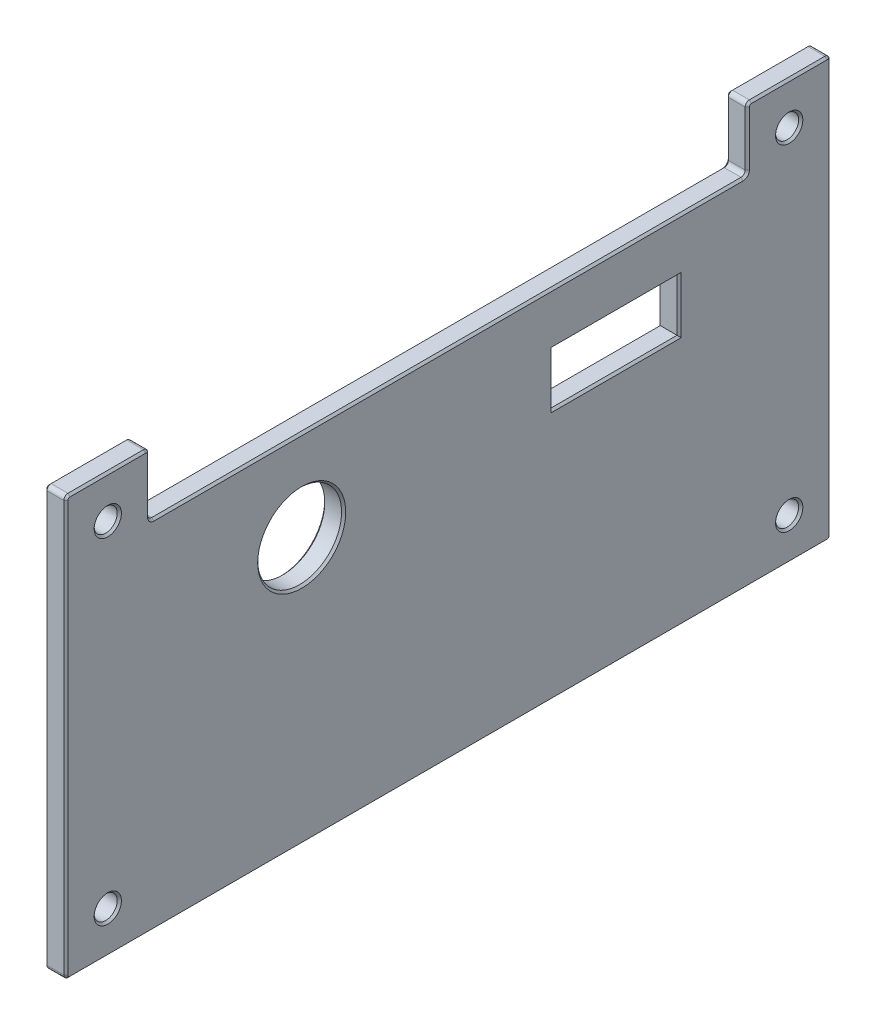
SolidWorks part; units mm, degrees
ref_plane "前视基准面" through (0, 0, 0) normal (0, 0, 1) x (1, 0, 0)
ref_plane "上视基准面" through (0, 0, 0) normal (0, 1, 0) x (1, 0, 0)
ref_plane "右视基准面" through (0, 0, 0) normal (1, 0, 0) x (0, 0, -1)
sketch "草图1" plane through (0, 0, 0) normal (1, 0, 0) x (0, 0, -1)
  line L1 (0, 0) -> (73, 0)
  line L2 (0, 0) -> (0, 34)
  line L3 (0, 34) -> (73, 34)
  line L4 (73, 0) -> (73, 34)
  dimension "D1" = 73
  dimension "D2" = 34
extrude "凸台-拉伸1" add sketch "草图1" along normal blind 2
sketch "草图2" plane through (2, 0, 0) normal (1, 0, 0) x (0, 0, -1)
  line L0 (73, 0) -> (73, 34) construction
  line L1 (46.5, 29) -> (58.5, 29)
  line L2 (46.5, 29) -> (46.5, 24)
  line L3 (46.5, 24) -> (58.5, 24)
  line L4 (58.5, 29) -> (58.5, 24)
  line L5 (73, 34) -> (0, 34) construction
  line L6 (0, 34) -> (0, 0) construction
  circle A0 centre (22.5, 25.4) radius 4
  dimension "D5" = 8
  dimension "D1" = 12
  dimension "D2" = 5
  dimension "D3" = 14.5
  dimension "D4" = 5
  dimension "D6" = 22.5
  dimension "D7" = 8.6
extrude "切除-拉伸1" cut sketch "草图2" against normal blind 2
sketch "草图3" plane through (0, 0, 0) normal (-1, 0, 0) x (0, 0, 1)
  line L1 (-73, 34) -> (-65, 34)
  line L2 (-73, 34) -> (-73, 40)
  line L3 (-73, 40) -> (-65, 40)
  line L4 (-65, 34) -> (-65, 40)
  line L5 (0, 34) -> (-8, 34)
  line L6 (0, 34) -> (0, 40)
  line L7 (0, 40) -> (-8, 40)
  line L8 (-8, 34) -> (-8, 40)
extrude "凸台-拉伸2" add sketch "草图3" against normal blind 2
sketch "草图4" plane through (2, 0, 0) normal (1, 0, 0) x (0, 0, -1)
  circle A0 centre (4, 36) radius 1.1
  circle A1 centre (69, 36) radius 1.1
  circle A2 centre (69, 4) radius 1.1
  circle A3 centre (4, 4) radius 1.1
  dimension "D1" = 2.2
  dimension "D2" = 2.2
  dimension "D3" = 2.2
  dimension "D4" = 2.2
extrude "切除-拉伸2" cut sketch "草图4" against normal blind 2
fillet "圆角1" radius 0.4 8 edges at (1, 40, 0) (1, 40, -8) (1, 34, -8) (1, 34, -65) (1, 40, -65) (1, 40, -73) (1, 0, -73) (1, 0, 0)
chamfer "倒角1" distance 0.2 angle 45 50 edges at (0, 0, -36.5) (2, 0, -36.5) (0, 20, -73) (2, 20, -73) (0, 40, -69) (2, 40, -69) (0, 37, -65) (2, 37, -65) (0, 34, -36.5) (2, 34, -36.5) (0, 37, -8) (2, 37, -8) (0, 40, -4) (2, 40, -4) (2, 20, 0) (0, 20, 0) (0, 25.4, -26.5) (2, 25.4, -26.5) (2, 29, -52.5) (0, 29, -52.5) (2, 26.5, -58.5) (0, 26.5, -58.5) (2, 24, -52.5) (0, 24, -52.5) (2, 26.5, -46.5) (0, 26.5, -46.5) (0, 36, -5.1) (2, 36, -5.1) (0, 36, -70.1) (2, 36, -70.1) (0, 4, -70.1) (2, 4, -70.1) (0, 4, -5.1) (2, 4, -5.1) (2, 0.1172, -0.1172) (0, 0.1172, -0.1172) (2, 0.1172, -72.8828) (0, 0.1172, -72.8828) (2, 39.8828, -72.8828) (0, 39.8828, -72.8828) (2, 39.8828, -65.1172) (0, 39.8828, -65.1172) (2, 34.1172, -64.8828) (0, 34.1172, -64.8828) (2, 34.1172, -8.1172) (0, 34.1172, -8.1172) (2, 39.8828, -7.8828) (0, 39.8828, -7.8828) (2, 39.8828, -0.1172) (0, 39.8828, -0.1172)
equation "\"D3@草图2\"=14.5"
